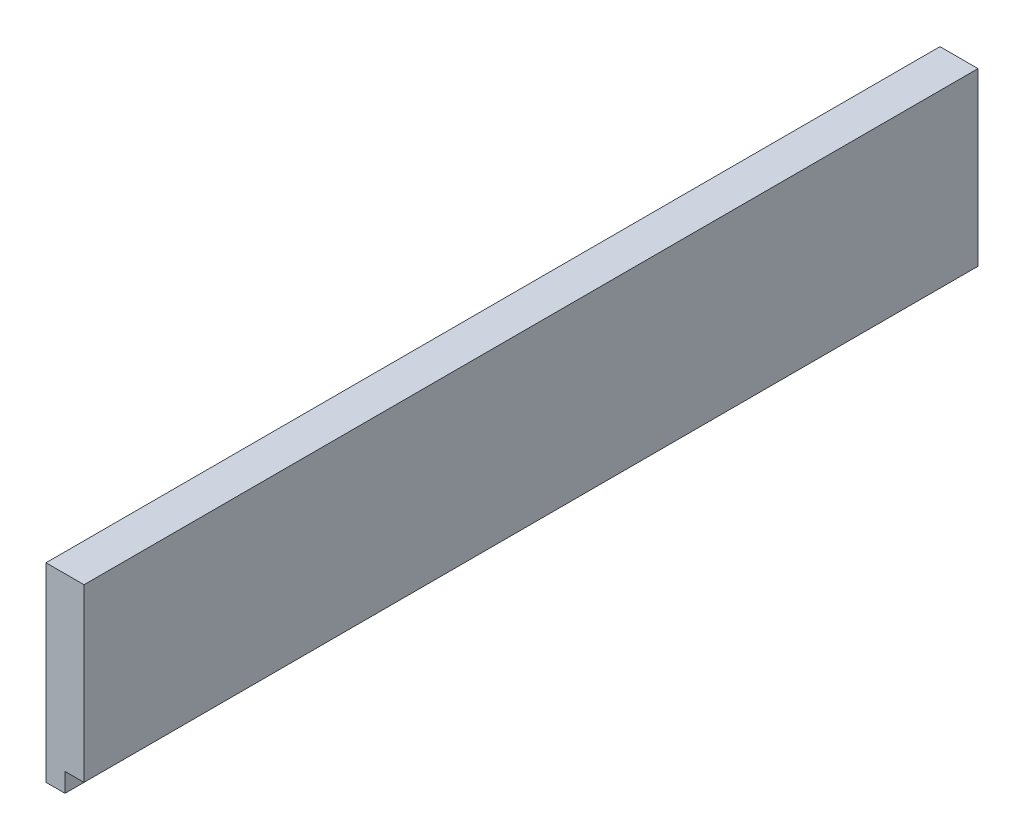
SolidWorks part; units mm, degrees
material "Сосна"
ref_plane "Спереди" through (0, 0, 0) normal (0, 0, 1) x (1, 0, 0)
ref_plane "Сверху" through (0, 0, 0) normal (0, 1, 0) x (1, 0, 0)
ref_plane "Справа" through (0, 0, 0) normal (1, 0, 0) x (0, 0, -1)
sketch "Эскиз1" plane through (0, 0, 0) normal (0, 0, 1) x (1, 0, 0)
  line L0 (0, 0) -> (0, 100)
  line L3 (0, 100) -> (20, 100)
  line L4 (20, 100) -> (20, 10)
  line L5 (20, 10) -> (10, 10)
  line L6 (10, 10) -> (10, 0)
  line L7 (10, 0) -> (0, 0)
  dimension "D1" = 100
  dimension "D2" = 20
  dimension "D3" = 10
  dimension "D4" = 10
extrude "Бобышка-Вытянуть1" add sketch "Эскиз1" along normal blind 470
